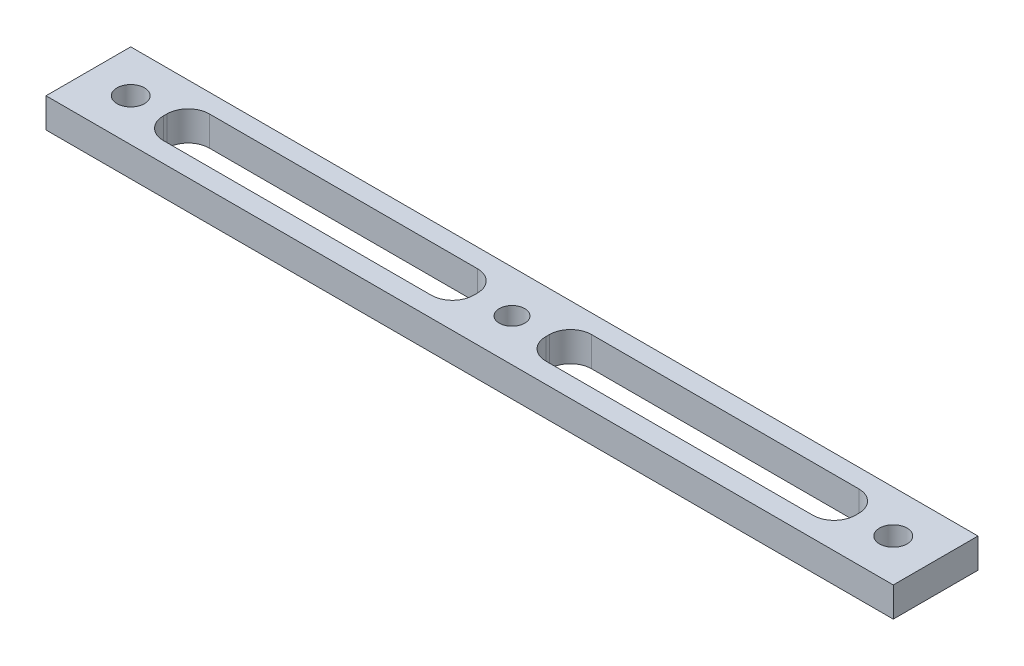
SolidWorks part; units mm, degrees
ref_plane "Płaszczyzna przednia" through (0, 0, 0) normal (0, 0, 1) x (1, 0, 0)
ref_plane "Płaszczyzna górna" through (0, 0, 0) normal (0, 1, 0) x (1, 0, 0)
ref_plane "Płaszczyzna prawa" through (0, 0, 0) normal (1, 0, 0) x (0, 0, -1)
sketch "Szkic1" plane through (0, 0, 0) normal (0, 1, 0) x (1, 0, 0)
  line L0 (100, 0) -> (100, 10)
  line L1 (0, 0) -> (200, 0)
  line L2 (0, 0) -> (0, 20)
  line L3 (0, 20) -> (200, 20)
  line L4 (200, 0) -> (200, 20)
  line L5 (0, 10) -> (10, 10)
  line L6 (200, 10) -> (190, 10)
  line L8 (22.9848, 15.5746) -> (86.2594, 15.5746)
  line L9 (17.9848, 10.5746) -> (17.9848, 9.6967)
  line L10 (22.9848, 4.6967) -> (86.2594, 4.6967)
  line L11 (91.2594, 10.5746) -> (91.2594, 9.6967)
  line L12 (113.2251, 15.5746) -> (176.2862, 15.5746)
  line L13 (108.2251, 10.5746) -> (108.2251, 9.7528)
  line L14 (113.2251, 4.7528) -> (176.2862, 4.7528)
  line L15 (181.2862, 10.5746) -> (181.2862, 9.7528)
  circle A0 centre (100, 10) radius 3
  circle A1 centre (10, 10) radius 3.25
  circle A2 centre (190, 10) radius 3.25
  arc A3 (176.2862, 4.7528) -> (181.2862, 9.7528) centre (176.2862, 9.7528) ccw
  arc A4 (181.2862, 10.5746) -> (176.2862, 15.5746) centre (176.2862, 10.5746) ccw
  arc A5 (113.2251, 4.7528) -> (108.2251, 9.7528) centre (113.2251, 9.7528) cw
  arc A6 (113.2251, 15.5746) -> (108.2251, 10.5746) centre (113.2251, 10.5746) ccw
  arc A7 (17.9848, 9.6967) -> (22.9848, 4.6967) centre (22.9848, 9.6967) ccw
  arc A8 (86.2594, 4.6967) -> (91.2594, 9.6967) centre (86.2594, 9.6967) ccw
  arc A9 (91.2594, 10.5746) -> (86.2594, 15.5746) centre (86.2594, 10.5746) ccw
  arc A10 (22.9848, 15.5746) -> (17.9848, 10.5746) centre (22.9848, 10.5746) ccw
  dimension "D1" = 5
extrude "Dodanie-wyciągnięcie1" add sketch "Szkic1" along normal blind 7
